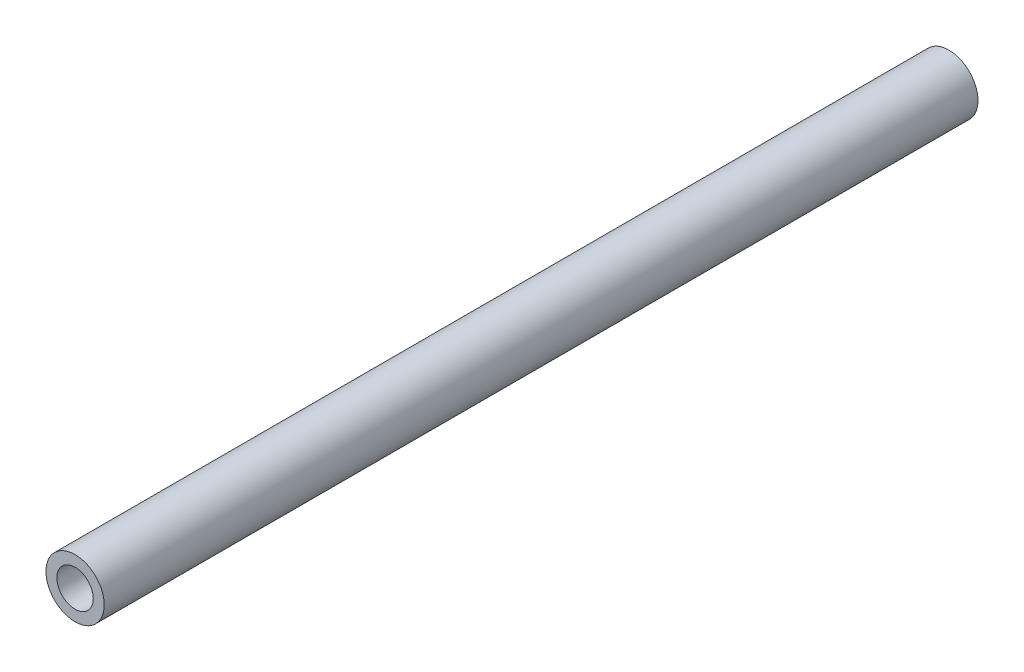
SolidWorks part; units mm, degrees
material "1.0545 (S355N)"
ref_plane "Płaszczyzna przednia" through (0, 0, 0) normal (0, 0, 1) x (1, 0, 0)
ref_plane "Płaszczyzna górna" through (0, 0, 0) normal (0, 1, 0) x (1, 0, 0)
ref_plane "Płaszczyzna prawa" through (0, 0, 0) normal (1, 0, 0) x (0, 0, -1)
sketch "Szkic1" plane through (0, 0, 0) normal (0, 0, 1) x (1, 0, 0)
  circle A0 centre (0, 0) radius 8
  circle A1 centre (0, 0) radius 4
  dimension "D1" = 16
  dimension "D2" = 4
extrude "Dodanie-wyciągnięcie1" add sketch "Szkic1" along normal mid plane 240
sketch "Szkic2" plane through (0, 0, 120) normal (0, 0, 1) x (1, 0, 0)
  circle A0 centre (0, 0) radius 5
  circle A2 centre (0, 0) radius 4 construction
  dimension "D1" = 1
extrude "Wytnij-wyciągnięcie1" cut sketch "Szkic2" against normal blind 40
sketch "Szkic3" plane through (0, 0, -120) normal (0, 0, -1) x (-1, 0, 0)
  circle A0 centre (0, 0) radius 5
  circle A1 centre (0, 0) radius 4 construction
  dimension "D1" = 1
extrude "Wytnij-wyciągnięcie2" cut sketch "Szkic3" against normal blind 30
